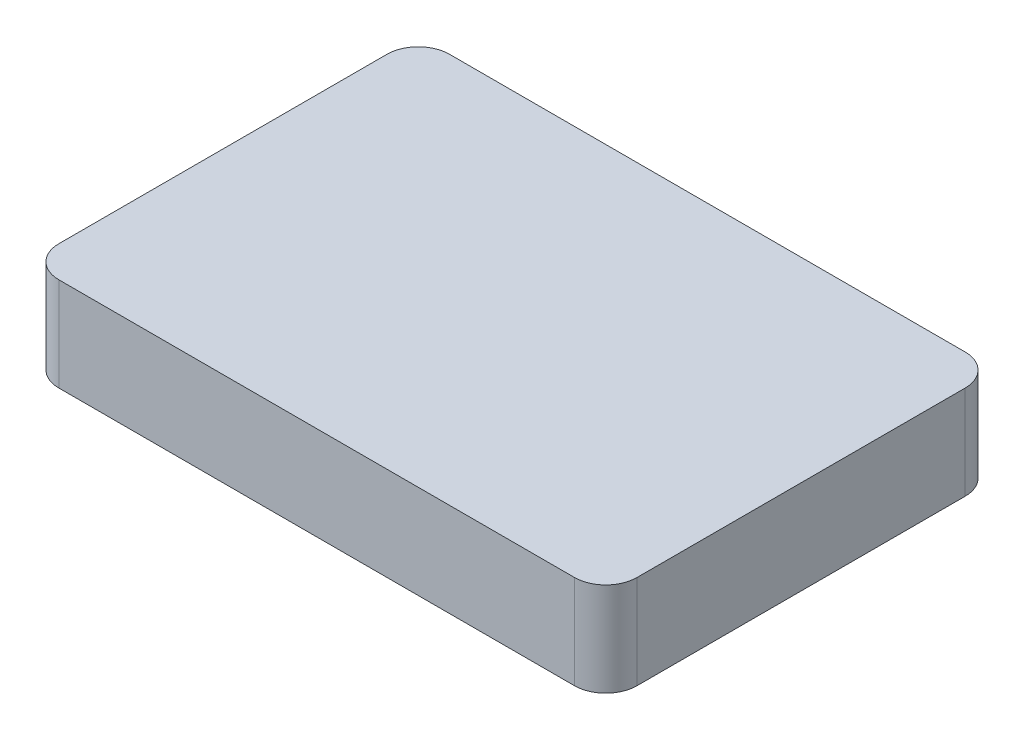
SolidWorks part; units mm, degrees
ref_plane "Front Plane" through (0, 0, 0) normal (0, 0, 1) x (1, 0, 0)
ref_plane "Top Plane" through (0, 0, 0) normal (0, 1, 0) x (1, 0, 0)
ref_plane "Right Plane" through (0, 0, 0) normal (1, 0, 0) x (0, 0, -1)
sketch "Sketch1" plane through (0, 0, 0) normal (0, 1, 0) x (1, 0, 0)
  line L1 (16.5, -12.5) -> (-16.5, -12.5)
  line L2 (18.5, -10.5) -> (18.5, 10.5)
  line L3 (16.5, 12.5) -> (-16.5, 12.5)
  line L4 (-18.5, -10.5) -> (-18.5, 10.5)
  line L5 (18.5, -12.5) -> (-18.5, 12.5) construction
  line L6 (18.5, 12.5) -> (-18.5, -12.5) construction
  arc A0 (-16.5, -12.5) -> (-18.5, -10.5) centre (-16.5, -10.5) cw
  arc A1 (16.5, -12.5) -> (18.5, -10.5) centre (16.5, -10.5) ccw
  arc A2 (18.5, 10.5) -> (16.5, 12.5) centre (16.5, 10.5) ccw
  arc A3 (-16.5, 12.5) -> (-18.5, 10.5) centre (-16.5, 10.5) ccw
  point P0 (0, 0)
  dimension "D3" = 2
  dimension "D1" = 37
  dimension "D2" = 25
extrude "Boss-Extrude1" add sketch "Sketch1" along normal blind 6
